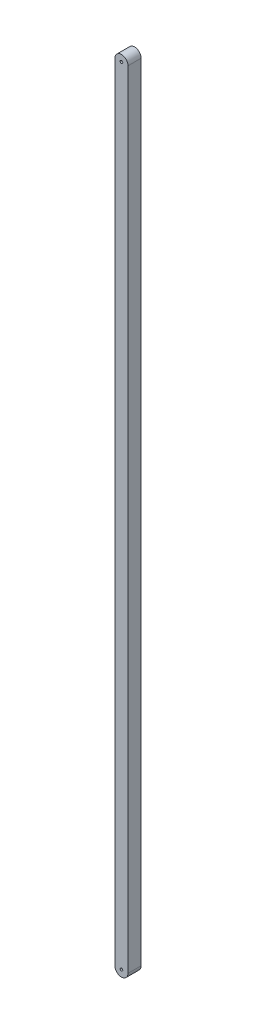
SolidWorks part; units mm, degrees
material "Nylon 6/10"
ref_plane "Front Plane" through (0, 0, 0) normal (0, 0, 1) x (1, 0, 0)
ref_plane "Top Plane" through (0, 0, 0) normal (0, 1, 0) x (1, 0, 0)
ref_plane "Right Plane" through (0, 0, 0) normal (1, 0, 0) x (0, 0, -1)
sketch "Sketch3" plane through (0, 0, 0) normal (0, 0, 1) x (1, 0, 0)
  line L0 (-0.5, 30) -> (0.5, -30) construction
  line L2 (-0.5, 30) -> (-0.5, -30)
  line L4 (0.5, 30) -> (0.5, -30)
  arc A0 (-0.5, 30) -> (0.5, 30) centre (0, 30) cw
  arc A1 (-0.5, -30) -> (0.5, -30) centre (0, -30) ccw
  circle A2 centre (0, 30) radius 0.1
  circle A3 centre (0, -30) radius 0.1
  dimension "D2" = 0.5
  dimension "D3" = 0.2
  dimension "D1" = 60
extrude "Extrude1" add sketch "Sketch3" along normal mid plane 1
